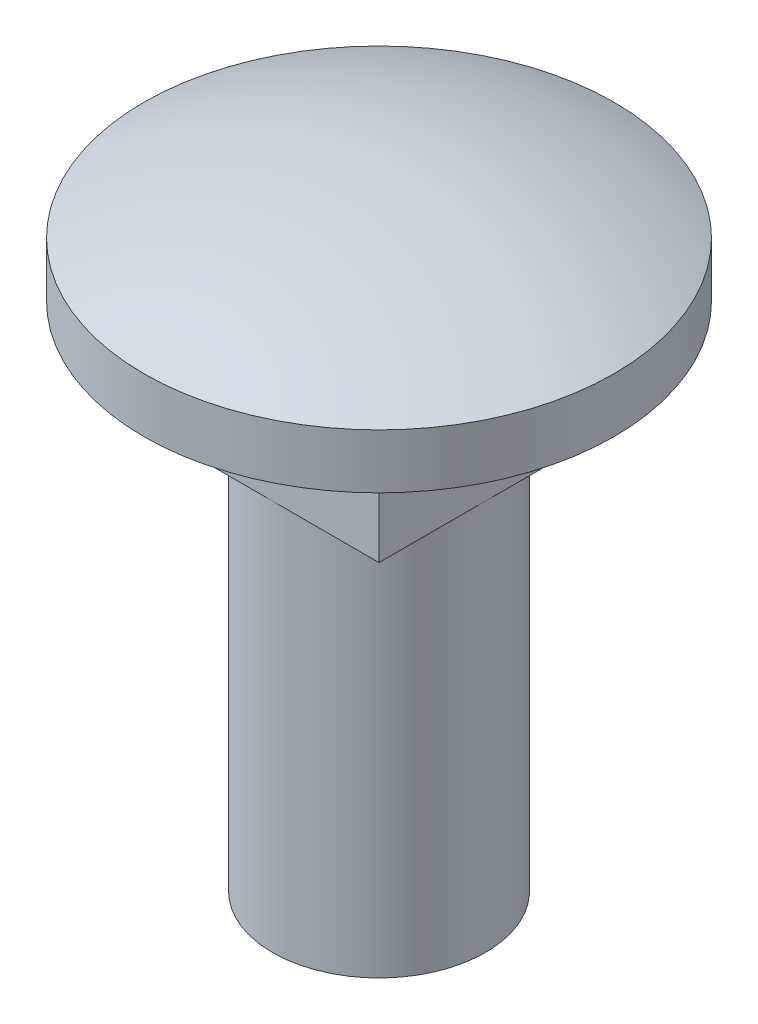
SolidWorks part; units mm, degrees
ref_plane "Front"
ref_plane "Top" through (0, 0, 0) normal (0, 1, 0) x (1, 0, 0)
ref_plane "Right" through (0, 0, 0) normal (1, 0, 0) x (0, 0, -1)
sketch "Sketch1" plane through (0, 0, 0) normal (0, 0, 1) x (1, 0, 0)
  line L0 (0, 0) -> (3.9688, 0)
  line L1 (3.9688, 0) -> (3.9688, 19.05)
  line L2 (3.9688, 19.05) -> (8.763, 19.05)
  line L3 (0, 23.114) -> (6.9428, 23.114) construction
  line L4 (8.763, 21.082) -> (8.763, 19.05)
  line L5 (0, 0) -> (0, 23.114)
  line L6 (0, 0) -> (0, 30.7805) construction
  arc A0 (8.763, 21.082) -> (0, 23.114) centre (0, 3.2028) ccw
  dimension "D1" = 23.114
  dimension "MajorDia" = 7.9375
  dimension "D2" = 17.526
  dimension "Length" = 19.05
  dimension "D3" = 2.032
revolve "Screw revolve" add sketch "Sketch1" angle 360 about L6
sketch "Sketch2" plane through (0, 19.05, 0) normal (0, -1, 0) x (1, 0, 0)
  line L0 (-4.0005, 4.0005) -> (4.0005, -4.0005) construction
  line L1 (-4.0005, 4.0005) -> (4.0005, 4.0005)
  line L2 (-4.0005, 4.0005) -> (-4.0005, -4.0005)
  line L3 (-4.0005, -4.0005) -> (4.0005, -4.0005)
  line L4 (4.0005, 4.0005) -> (4.0005, -4.0005)
  point P4 (0, 0)
  dimension "D1" = 8.001
extrude "Square boss" add sketch "Sketch2" along normal blind 4.445
